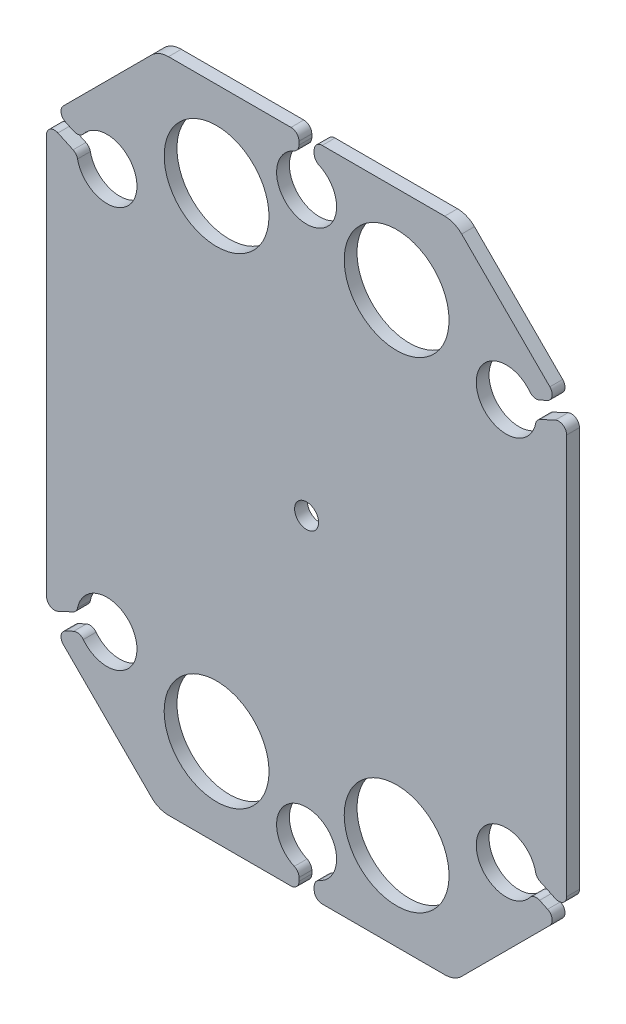
SolidWorks part; units mm, degrees
ref_plane "Ön Düzlem" through (0, 0, 0) normal (0, 0, 1) x (1, 0, 0)
ref_plane "Üst Düzlem" through (0, 0, 0) normal (0, 1, 0) x (1, 0, 0)
ref_plane "Sağ Düzlem" through (0, 0, 0) normal (1, 0, 0) x (0, 0, -1)
sketch "Çizim1" plane through (0, 0, 0) normal (0, 0, 1) x (1, 0, 0)
  line L0 (51.8787, -0.8787) -> (62.9014, -11.9014)
  line L1 (15.2426, 0) -> (30.55, 0)
  line L2 (0, -16.0697) -> (0, -29) construction
  line L3 (2, -31) -> (7.4942, -31) construction
  line L4 (65, -16.0697) -> (65, -29) construction
  line L5 (2.0986, -11.9014) -> (13.1213, -0.8787)
  line L6 (15.8302, -16) -> (49.1698, -16) construction
  line L7 (31.55, -1.4187) -> (31.55, -1)
  line L8 (33.45, -1.4187) -> (33.45, -1)
  line L9 (34.45, 0) -> (49.7574, 0)
  line L10 (57.5058, -31) -> (63, -31) construction
  line L11 (3.3844, -13.9818) -> (2.3831, -13.5148)
  line L12 (3.3194, -16.0479) -> (1.4226, -15.1634)
  line L13 (32.5, -41.343) -> (32.5, -25.2413) construction
  line L14 (61.6156, -13.9818) -> (62.6169, -13.5148)
  line L15 (61.6806, -16.0479) -> (63.5774, -15.1634)
  line L16 (-4.2968, -41.05) -> (39.0777, -41.05) construction
  line L17 (57.5058, -51.1) -> (63, -51.1) construction
  line L18 (15.8302, -66.1) -> (49.1698, -66.1) construction
  line L19 (65, -66.0303) -> (65, -53.1) construction
  line L20 (2, -51.1) -> (7.4942, -51.1) construction
  line L21 (0, -66.0303) -> (0, -53.1) construction
  line L22 (61.6806, -66.0521) -> (63.5774, -66.9366)
  line L23 (61.6156, -68.1182) -> (62.6169, -68.5852)
  line L24 (3.3194, -66.0521) -> (1.4226, -66.9366)
  line L25 (3.3844, -68.1182) -> (2.3831, -68.5852)
  line L26 (34.45, -82.1) -> (49.7574, -82.1)
  line L27 (33.45, -80.6813) -> (33.45, -81.1)
  line L28 (31.55, -80.6813) -> (31.55, -81.1)
  line L29 (2.0986, -70.1986) -> (13.1213, -81.2213)
  line L30 (15.2426, -82.1) -> (30.55, -82.1)
  line L31 (51.8787, -81.2213) -> (62.9014, -70.1986)
  line L32 (0, -66.0303) -> (0, -16.0697)
  line L33 (65, -66.0303) -> (65, -16.0697)
  arc A0 (10.141, -29.4123) -> (54.859, -29.4123) centre (32.5, -41.343) cw construction
  arc A1 (30.9605, -2.3306) -> (34.0395, -2.3306) centre (32.5, -5.75) ccw
  arc A2 (3.8764, -16.7533) -> (4.595, -13.6912) centre (7.55, -16) ccw
  arc A3 (60.405, -13.6912) -> (61.1236, -16.7533) centre (57.45, -16) ccw
  circle A4 centre (21.25, -11) radius 6.55
  circle A5 centre (43.75, -11) radius 6.55
  arc A6 (33.45, -1.4187) -> (34.0395, -2.3306) centre (34.45, -1.4187) ccw
  arc A7 (31.55, -1.4187) -> (30.9605, -2.3306) centre (30.55, -1.4187) cw
  arc A8 (33.45, -1) -> (34.45, 0) centre (34.45, -1) cw
  arc A9 (31.55, -1) -> (30.55, 0) centre (30.55, -1) ccw
  arc A10 (61.6156, -13.9818) -> (60.405, -13.6912) centre (61.1929, -13.0755) cw
  arc A11 (61.6806, -16.0479) -> (61.1236, -16.7533) centre (62.1032, -16.9542) ccw
  arc A12 (63.5774, -15.1634) -> (65, -16.0697) centre (64, -16.0697) cw
  arc A13 (62.6169, -13.5148) -> (62.9014, -11.9014) centre (62.1943, -12.6085) ccw
  arc A14 (3.3844, -13.9818) -> (4.595, -13.6912) centre (3.8071, -13.0755) ccw
  arc A15 (3.3194, -16.0479) -> (3.8764, -16.7533) centre (2.8968, -16.9542) cw
  arc A16 (2.3831, -13.5148) -> (2.0986, -11.9014) centre (2.8057, -12.6085) cw
  arc A17 (1.4226, -15.1634) -> (0, -16.0697) centre (1, -16.0697) ccw
  arc A18 (51.8787, -0.8787) -> (49.7574, 0) centre (49.7574, -3) ccw
  arc A19 (13.1213, -0.8787) -> (15.2426, 0) centre (15.2426, -3) cw
  arc A20 (54.859, -29.4123) -> (57.5058, -31) centre (57.5058, -28) ccw construction
  arc A21 (10.141, -29.4123) -> (7.4942, -31) centre (7.4942, -28) cw construction
  arc A22 (63, -31) -> (65, -29) centre (63, -29) ccw construction
  arc A23 (0, -29) -> (2, -31) centre (2, -29) ccw construction
  arc A24 (0, -53.1) -> (2, -51.1) centre (2, -53.1) cw construction
  arc A25 (63, -51.1) -> (65, -53.1) centre (63, -53.1) cw construction
  arc A26 (10.141, -52.6877) -> (7.4942, -51.1) centre (7.4942, -54.1) ccw construction
  arc A27 (54.859, -52.6877) -> (57.5058, -51.1) centre (57.5058, -54.1) cw construction
  arc A28 (10.141, -52.6877) -> (54.859, -52.6877) centre (32.5, -40.757) ccw construction
  arc A29 (13.1213, -81.2213) -> (15.2426, -82.1) centre (15.2426, -79.1) ccw
  arc A30 (51.8787, -81.2213) -> (49.7574, -82.1) centre (49.7574, -79.1) cw
  arc A31 (1.4226, -66.9366) -> (0, -66.0303) centre (1, -66.0303) cw
  arc A32 (2.3831, -68.5852) -> (2.0986, -70.1986) centre (2.8057, -69.4915) ccw
  arc A33 (3.3194, -66.0521) -> (3.8764, -65.3467) centre (2.8968, -65.1458) ccw
  arc A34 (3.3844, -68.1182) -> (4.595, -68.4088) centre (3.8071, -69.0245) cw
  arc A35 (62.6169, -68.5852) -> (62.9014, -70.1986) centre (62.1943, -69.4915) cw
  arc A36 (63.5774, -66.9366) -> (65, -66.0303) centre (64, -66.0303) ccw
  arc A37 (61.6806, -66.0521) -> (61.1236, -65.3467) centre (62.1032, -65.1458) cw
  arc A38 (61.6156, -68.1182) -> (60.405, -68.4088) centre (61.1929, -69.0245) ccw
  arc A39 (31.55, -81.1) -> (30.55, -82.1) centre (30.55, -81.1) cw
  arc A40 (33.45, -81.1) -> (34.45, -82.1) centre (34.45, -81.1) ccw
  arc A41 (31.55, -80.6813) -> (30.9605, -79.7694) centre (30.55, -80.6813) ccw
  arc A42 (33.45, -80.6813) -> (34.0395, -79.7694) centre (34.45, -80.6813) cw
  circle A43 centre (43.75, -71.1) radius 6.55
  circle A44 centre (21.25, -71.1) radius 6.55
  arc A45 (60.405, -68.4088) -> (61.1236, -65.3467) centre (57.45, -66.1) cw
  arc A46 (3.8764, -65.3467) -> (4.595, -68.4088) centre (7.55, -66.1) cw
  arc A47 (30.9605, -79.7694) -> (34.0395, -79.7694) centre (32.5, -76.35) cw
  point P0 (0, 0)
  point P3 (65, 0)
  point P37 (33.45, 0)
  point P42 (60.8191, -14.3532)
  point P45 (61.1898, -16.2767)
  point P50 (63.9113, -12.9113)
  point P53 (4.1809, -14.3532)
  point P57 (3.8102, -16.2767)
  point P60 (1.0887, -12.9113)
  point P63 (0, -14.5)
  point P66 (51, 0)
  point P69 (14, 0)
  point P72 (55.6363, -31)
  point P75 (9.3637, -31)
  point P80 (0, -31)
  point P147 (0, -51.1)
  point P148 (9.3637, -51.1)
  point P149 (55.6363, -51.1)
  point P150 (14, -82.1)
  point P151 (51, -82.1)
  point P152 (0, -67.6)
  point P153 (1.0887, -69.1887)
  point P154 (3.8102, -65.8233)
  point P155 (4.1809, -67.7468)
  point P156 (63.9113, -69.1887)
  point P157 (61.1898, -65.8233)
  point P158 (60.8191, -67.7468)
  point P159 (33.45, -82.1)
  point P160 (65, -82.1)
  point P161 (0, -82.1)
  dimension "D7" = 7.5
  dimension "D8" = 13.1
  dimension "D9" = 11
  dimension "D10" = 22.5
  dimension "D11" = 32.5
  dimension "D12" = 5.75
  dimension "D15" = 21.25
  dimension "D17" = 7.55
  dimension "D18" = 7.55
  dimension "D19" = 15
  dimension "D25" = 1
  dimension "D26" = 3
  dimension "D27" = 2
  dimension "D1" = 31
  dimension "D2" = 65
  dimension "D24" = 65
  dimension "D23" = 18.2593
  dimension "D3" = 46.2726
  dimension "D4" = 16
  dimension "D13" = 1.9
  dimension "D14" = 0.95
  dimension "D16" = 9.3637
  dimension "D20" = 1.9
  dimension "D21" = 65
  dimension "D22" = 16.5
  dimension "D28" = 41.05
extrude "Yükseklik-Ekstrüzyon1" add sketch "Çizim1" along normal blind 1.6
sketch "Çizim2" plane through (0, 0, 1.6) normal (0, 0, 1) x (1, 0, 0)
  line L0 (65, -66.0303) -> (65, -16.0697) construction
  circle A0 centre (32.5, -41.05) radius 1.5
  arc A1 (34.0395, -79.7694) -> (30.9605, -79.7694) centre (32.5, -76.35) ccw construction
  point P2 (0, 0)
  point P5 (65, -41.05)
  point P9 (32.5, -72.6)
  dimension "D1" = 3
extrude "Kes-Ekstrüzyon1" cut sketch "Çizim2" against normal up to surface (1.6 mm away) up to face at (32.5, -41.05, 0)
